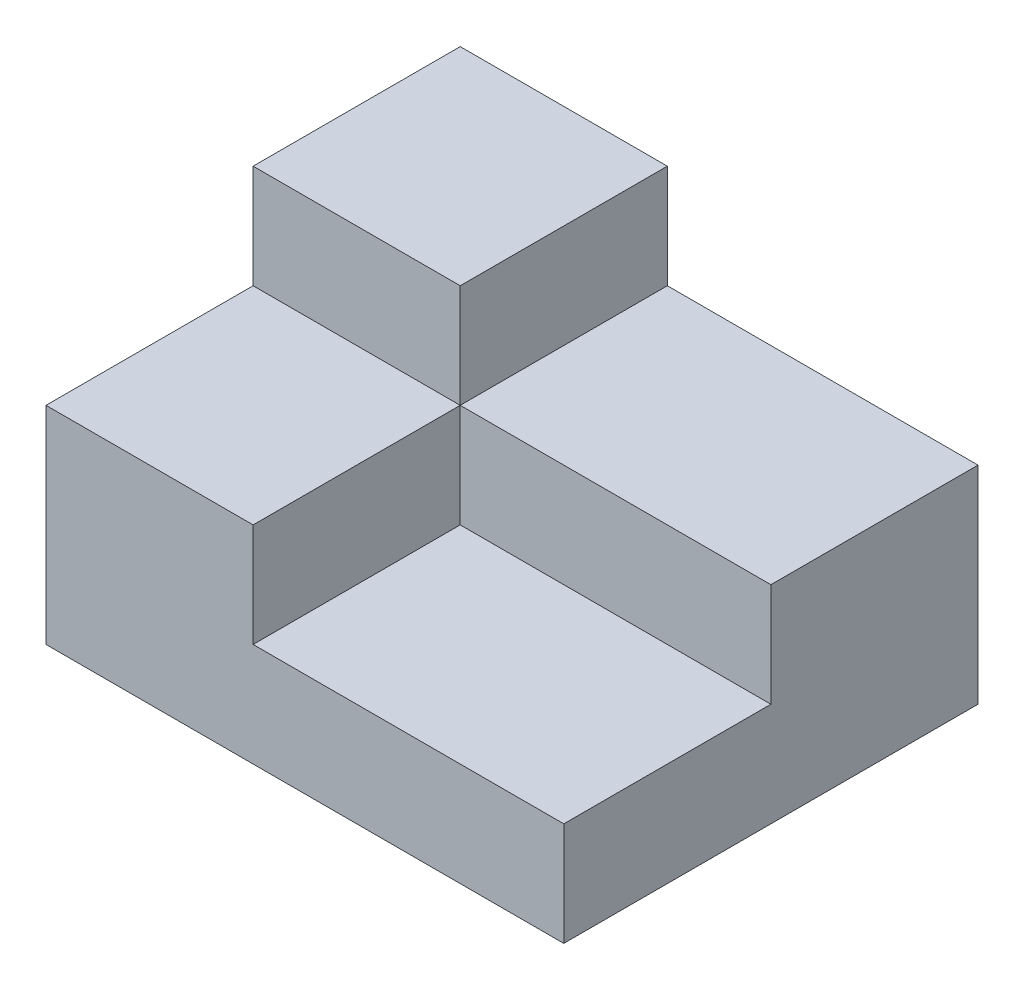
SolidWorks part; units mm, degrees
ref_plane "Front Plane" through (0, 0, 0) normal (0, 0, 1) x (1, 0, 0)
ref_plane "Top Plane" through (0, 0, 0) normal (0, 1, 0) x (1, 0, 0)
ref_plane "Right Plane" through (0, 0, 0) normal (1, 0, 0) x (0, 0, -1)
sketch "Sketch1" plane through (0, 0, 0) normal (0, 1, 0) x (1, 0, 0)
  line L1 (-63.5, -50.8) -> (63.5, -50.8)
  line L2 (-63.5, -50.8) -> (-63.5, 50.8)
  line L3 (-63.5, 50.8) -> (63.5, 50.8)
  line L4 (63.5, -50.8) -> (63.5, 50.8)
  line L5 (-63.5, -50.8) -> (63.5, 50.8) construction
  line L6 (-63.5, 50.8) -> (63.5, -50.8) construction
  point P0 (0, 0)
  dimension "D1" = 101.6
  dimension "D2" = 127
extrude "Boss-Extrude1" add sketch "Sketch1" along normal blind 25.4
sketch "Sketch2" plane through (0, 25.4, 0) normal (0, 1, 0) x (1, 0, 0)
  line L0 (-63.5, -50.8) -> (63.5, -50.8) construction
  line L1 (-63.5, 50.8) -> (-35.6026, 50.8)
  line L2 (-63.5, 50.8) -> (-63.5, -50.8)
  line L3 (-63.5, -50.8) -> (-12.7, -50.8)
  line L4 (-12.7, 0) -> (-12.7, -50.8)
  line L5 (63.5, -50.8) -> (63.5, 50.8) construction
  line L6 (63.5, 50.8) -> (-35.6026, 50.8)
  line L7 (63.5, 50.8) -> (63.5, 0)
  line L8 (63.5, 0) -> (-12.7, 0)
  dimension "D1" = 76.2
  dimension "D2" = 50.8
extrude "Boss-Extrude2" add sketch "Sketch2" along normal blind 25.4
sketch "Sketch3" plane through (0, 50.8, 0) normal (0, 1, 0) x (1, 0, 0)
  line L1 (-63.5, 50.8) -> (-12.7, 50.8)
  line L2 (-63.5, 50.8) -> (-63.5, 0)
  line L3 (-63.5, 0) -> (-12.7, 0)
  line L4 (-12.7, 50.8) -> (-12.7, 0)
extrude "Boss-Extrude3" add sketch "Sketch3" along normal blind 25.4
